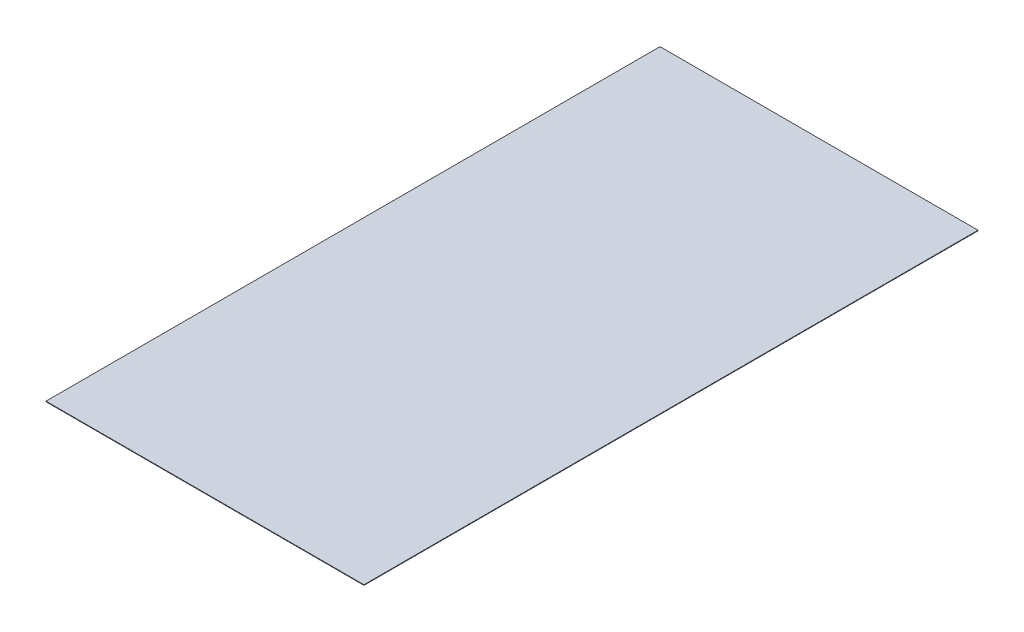
SolidWorks part; units mm, degrees
ref_plane "Front Plane" through (0, 0, 0) normal (0, 0, 1) x (1, 0, 0)
ref_plane "Top Plane" through (0, 0, 0) normal (0, 1, 0) x (1, 0, 0)
ref_plane "Right Plane" through (0, 0, 0) normal (1, 0, 0) x (0, 0, -1)
sketch "Esquisse1" plane through (0, 0, 0) normal (0, 1, 0) x (1, 0, 0)
  line L1 (-2900, 5600) -> (2900, 5600)
  line L2 (-2900, 5600) -> (-2900, -5600)
  line L3 (-2900, -5600) -> (2900, -5600)
  line L4 (2900, 5600) -> (2900, -5600)
  line L5 (-2900, 5600) -> (2900, -5600) construction
  line L6 (-2900, -5600) -> (2900, 5600) construction
  point P0 (0, 0)
extrude "Boss.-Extru.1" add sketch "Esquisse1" along normal blind 10
